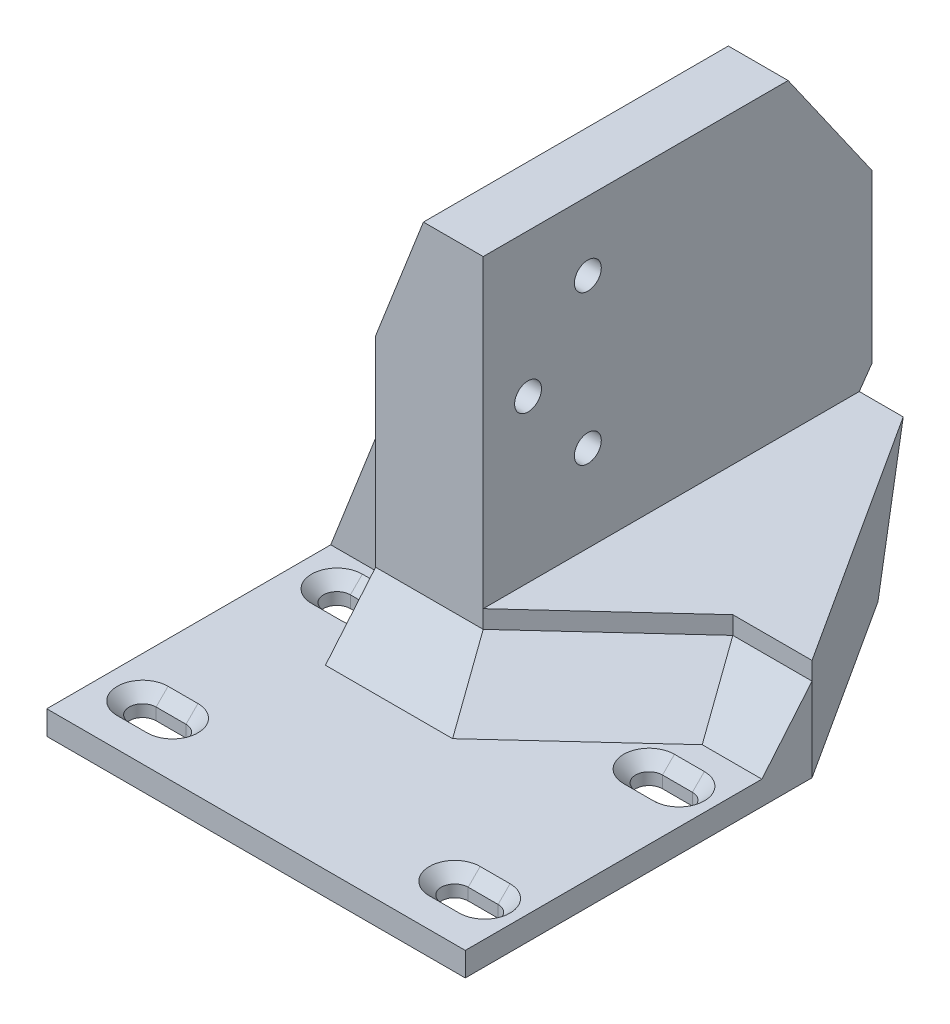
SolidWorks part; units mm, degrees
material "ABS"
ref_plane "Front Plane" through (0, 0, 0) normal (0, 0, 1) x (1, 0, 0)
ref_plane "Top Plane" through (0, 0, 0) normal (0, 1, 0) x (1, 0, 0)
ref_plane "Right Plane" through (0, 0, 0) normal (1, 0, 0) x (0, 0, -1)
sketch "Sketch1" plane through (0, 0, 0) normal (0, 1, 0) x (1, 0, 0)
  line L0 (-35, 29) -> (0, 74)
  line L2 (35, 29) -> (35, -29)
  line L3 (35, -29) -> (-35, -29)
  line L4 (-35, 29) -> (-35, -29)
  line L5 (35, 29) -> (-35, -29) construction
  line L6 (35, -29) -> (-35, 29) construction
  line L7 (0, 74) -> (6, 74)
  line L8 (6, 74) -> (35, 29)
  point P0 (0, 0)
  dimension "D1" = 70
  dimension "D2" = 58
  dimension "D3" = 6
  dimension "D4" = 29
  dimension "D5" = 103
  dimension "D6" = 35
extrude "Boss-Extrude1" add sketch "Sketch1" along normal blind 4
sketch "Sketch2" plane through (0, 4, 0) normal (0, 1, 0) x (1, 0, 0)
  line L0 (35, 29) -> (21.75, 29)
  line L1 (21.75, 29) -> (0, 9)
  line L2 (0, 9) -> (-18, 9)
  line L3 (-18, 9) -> (-18, 18.5)
  line L4 (-18, 18.5) -> (-35, 18.5)
  line L5 (-35, 29) -> (-35, -29) construction
  line L6 (-35, 18.5) -> (-35, 29)
  line L7 (-35, 29) -> (0, 74)
  line L8 (0, 74) -> (6, 74)
  line L9 (6, 74) -> (35, 29)
  line L10 (-35, -29) -> (35, -29) construction
  dimension "D1" = 17
  dimension "D2" = 47.5
  dimension "D3" = 38
  dimension "D4" = 18
  dimension "D5" = 13.25
extrude "Boss-Extrude2" add sketch "Sketch2" along normal blind 64
sketch "Sketch3" plane through (0, 0, -9) normal (0, 0, 1) x (1, 0, 0)
  line L0 (-35, 4) -> (-10, 68)
  line L1 (-18, 68) -> (0, 68) construction
  line L2 (-10, 68) -> (-35, 68)
  line L3 (-35, 68) -> (-35, 4)
  line L4 (0, 68) -> (0, 17)
  line L5 (0, 68) -> (0, 4) construction
  line L6 (0, 17) -> (35, 17)
  line L7 (35, 68) -> (35, 4) construction
  line L8 (35, 17) -> (35, 68)
  line L9 (35, 68) -> (0, 68)
  dimension "D1" = 25
  dimension "D2" = 51
extrude "Cut-Extrude1" cut sketch "Sketch3" against normal through all
sketch "Sketch4" plane through (35, 0, 0) normal (1, 0, 0) x (0, 0, -1)
  line L0 (60, 0) -> (74, 20)
  line L1 (29, 0) -> (74, 0) construction
  line L2 (74, 68) -> (74, 17) construction
  line L3 (74, 20) -> (74, 0)
  line L4 (74, 0) -> (60, 0)
  line L5 (60, 68) -> (74, 68)
  line L6 (74, 68) -> (9, 68) construction
  line L7 (74, 68) -> (74, 48)
  line L8 (74, 48) -> (60, 68)
  dimension "D1" = 20
  dimension "D2" = 14
  dimension "D3" = 20
  dimension "D4" = 14
extrude "Cut-Extrude2" cut sketch "Sketch4" against normal through all
chamfer "Chamfer1" distance 10 angle 40 3 edges at (-9, 4, -9) (10.875, 4, -19) (28.375, 4, -29)
sketch "Sketch5" plane through (0, 0, 0) normal (1, 0, 0) x (0, 0, -1)
  line L0 (26.5, 56.5) -> (26.5, 31.5) construction
  line L1 (9, 68) -> (9, 17) construction
  line L2 (60, 68) -> (9, 68) construction
  point P0 (16.5, 44)
  point P1 (26.5, 56.5)
  point P2 (26.5, 31.5)
  dimension "D1" = 10
  dimension "D2" = 25
  dimension "D3" = 12.5
  dimension "D4" = 7.5
  dimension "D5" = 24
hole_wizard "Ø4.5 (4.5) Diameter Hole1" positions "Sketch6" profile "Sketch8" hole size "Ø4.5" standard "ANSI Metric" end condition through all
sketch "Sketch6" plane through (0, 0, 0) normal (1, 0, 0) x (0, 0, -1)
  point P0 (16.5, 44)
  point P3 (26.5, 31.5)
  point P6 (26.5, 56.5)
sketch "Sketch8" plane through (0, 44, -16.5) normal (0, 1, 0) x (0, 0, -1)
  line L0 (0, 0) -> (0, 35)
  line L1 (0, 35) -> (2.25, 35)
  line L2 (2.25, 35) -> (2.25, 0)
  line L5 (2.25, 0) -> (0, 0)
  line L11 (0, -6.35) -> (0, 107.95) construction
  dimension "Thru Hole Dia." = 4.5
  dimension "Thru Hole Depth" = 35
ref_plane "Plane1" through (-5, 0, 0) normal (1, 0, 0) x (0, 0, -1)
sketch "Sketch9" plane through (-5, 0, 0) normal (1, 0, 0) x (0, 0, -1)
  line L0 (16.5, 44) -> (19.9641, 44) construction
  line L1 (29.9641, 56.5) -> (28.2321, 59.5)
  line L2 (28.2321, 59.5) -> (24.7679, 59.5)
  line L3 (24.7679, 59.5) -> (23.0359, 56.5)
  line L4 (23.0359, 56.5) -> (24.7679, 53.5)
  line L5 (24.7679, 53.5) -> (28.2321, 53.5)
  line L6 (28.2321, 53.5) -> (29.9641, 56.5)
  line L7 (29.9641, 31.5) -> (28.2321, 34.5)
  line L8 (28.2321, 34.5) -> (24.7679, 34.5)
  line L9 (24.7679, 34.5) -> (23.0359, 31.5)
  line L10 (23.0359, 31.5) -> (24.7679, 28.5)
  line L11 (24.7679, 28.5) -> (28.2321, 28.5)
  line L12 (28.2321, 28.5) -> (29.9641, 31.5)
  line L13 (19.9641, 44) -> (18.2321, 47)
  line L14 (18.2321, 47) -> (14.7679, 47)
  line L15 (14.7679, 47) -> (13.0359, 44)
  line L16 (13.0359, 44) -> (14.7679, 41)
  line L17 (14.7679, 41) -> (18.2321, 41)
  line L18 (18.2321, 41) -> (19.9641, 44)
  line L19 (26.5, 56.5) -> (29.9641, 56.5) construction
  line L20 (26.5, 31.5) -> (29.9641, 31.5) construction
  circle A0 centre (26.5, 56.5) radius 3 construction
  circle A1 centre (26.5, 31.5) radius 3 construction
  circle A2 centre (16.5, 44) radius 3 construction
  dimension "D1" = 6
  dimension "D2" = 6
  dimension "D3" = 6
extrude "Cut-Extrude3" cut sketch "Sketch9" against normal through all
ref_plane "Plane2" through (-10, 0, 0) normal (1, 0, 0) x (0, 0, -1)
sketch "Sketch10" plane through (-10, 0, 0) normal (1, 0, 0) x (0, 0, -1)
  line L0 (26.5, 56.5) -> (30.8879, 56.5) construction
  line L1 (30.8879, 56.5) -> (28.6939, 60.3)
  line L2 (28.6939, 60.3) -> (24.3061, 60.3)
  line L3 (24.3061, 60.3) -> (22.1121, 56.5)
  line L4 (22.1121, 56.5) -> (24.3061, 52.7)
  line L5 (24.3061, 52.7) -> (28.6939, 52.7)
  line L6 (28.6939, 52.7) -> (30.8879, 56.5)
  line L7 (20.8879, 44) -> (18.6939, 47.8)
  line L8 (18.6939, 47.8) -> (14.3061, 47.8)
  line L9 (14.3061, 47.8) -> (12.1121, 44)
  line L10 (12.1121, 44) -> (14.3061, 40.2)
  line L11 (14.3061, 40.2) -> (18.6939, 40.2)
  line L12 (18.6939, 40.2) -> (20.8879, 44)
  line L13 (30.8879, 31.5) -> (28.6939, 35.3)
  line L14 (28.6939, 35.3) -> (24.3061, 35.3)
  line L15 (24.3061, 35.3) -> (22.1121, 31.5)
  line L16 (22.1121, 31.5) -> (24.3061, 27.7)
  line L17 (24.3061, 27.7) -> (28.6939, 27.7)
  line L18 (28.6939, 27.7) -> (30.8879, 31.5)
  line L19 (16.5, 44) -> (20.8879, 44) construction
  line L20 (26.5, 31.5) -> (30.8879, 31.5) construction
  circle A0 centre (26.5, 56.5) radius 3.8 construction
  circle A1 centre (16.5, 44) radius 3.8 construction
  circle A2 centre (26.5, 31.5) radius 3.8 construction
  dimension "D1" = 7.6
  dimension "D2" = 7.6
  dimension "D3" = 7.6
extrude "Cut-Extrude4" cut sketch "Sketch10" against normal through all
sketch "Sketch11" plane through (0, 4, 0) normal (0, 1, 0) x (1, 0, 0)
  line L0 (-28.11, -19.85) -> (-23.11, -19.85) construction
  line L1 (-28.11, -17.6) -> (-23.11, -17.6)
  line L2 (-28.11, -22.1) -> (-23.11, -22.1)
  line L3 (24.09, -19.85) -> (29.09, -19.85) construction
  line L4 (24.09, -17.6) -> (29.09, -17.6)
  line L5 (24.09, -22.1) -> (29.09, -22.1)
  line L6 (-28.11, 12.65) -> (-23.11, 12.65) construction
  line L7 (-28.11, 14.9) -> (-23.11, 14.9)
  line L8 (-28.11, 10.4) -> (-23.11, 10.4)
  line L9 (24.09, 12.65) -> (29.09, 12.65) construction
  line L10 (24.09, 14.9) -> (29.09, 14.9)
  line L11 (24.09, 10.4) -> (29.09, 10.4)
  line L12 (-23.11, 12.65) -> (24.09, 12.65) construction
  line L13 (24.09, 12.65) -> (24.09, -19.85) construction
  line L14 (-23.11, 12.65) -> (-23.11, -19.85) construction
  line L15 (-35, -29) -> (35, -29) construction
  line L16 (35, -29) -> (35, 20.609) construction
  arc A0 (-28.11, -17.6) -> (-28.11, -22.1) centre (-28.11, -19.85) ccw
  arc A1 (-23.11, -22.1) -> (-23.11, -17.6) centre (-23.11, -19.85) ccw
  arc A2 (24.09, -17.6) -> (24.09, -22.1) centre (24.09, -19.85) ccw
  arc A3 (29.09, -22.1) -> (29.09, -17.6) centre (29.09, -19.85) ccw
  arc A4 (-28.11, 14.9) -> (-28.11, 10.4) centre (-28.11, 12.65) ccw
  arc A5 (-23.11, 10.4) -> (-23.11, 14.9) centre (-23.11, 12.65) ccw
  arc A6 (24.09, 14.9) -> (24.09, 10.4) centre (24.09, 12.65) ccw
  arc A7 (29.09, 10.4) -> (29.09, 14.9) centre (29.09, 12.65) ccw
  point P2 (-25.61, -19.85)
  point P7 (26.59, -19.85)
  point P14 (-25.61, 12.65)
  point P21 (26.59, 12.65)
  dimension "D2" = 2.25
  dimension "D4" = 2.25
  dimension "D6" = 2.25
  dimension "D8" = 2.25
  dimension "D1" = 5
  dimension "D3" = 5
  dimension "D5" = 5
  dimension "D7" = 5
  dimension "D9" = 52.2
  dimension "D10" = 32.5
  dimension "D11" = 6.9
  dimension "D12" = 5.91
extrude "Cut-Extrude5" cut sketch "Sketch11" against normal blind 10
chamfer "Chamfer3" distance 2 angle 45 16 edges at (-25.61, 4, -10.4) (-20.86, 4, -12.65) (-30.36, 4, -12.65) (-25.61, 4, -14.9) (-25.61, 4, 22.1) (-20.86, 4, 19.85) (-30.36, 4, 19.85) (-25.61, 4, 17.6) (26.59, 4, 22.1) (31.34, 4, 19.85) (21.84, 4, 19.85) (26.59, 4, 17.6) (26.59, 4, -10.4) (31.34, 4, -12.65) (21.84, 4, -12.65) (26.59, 4, -14.9)
